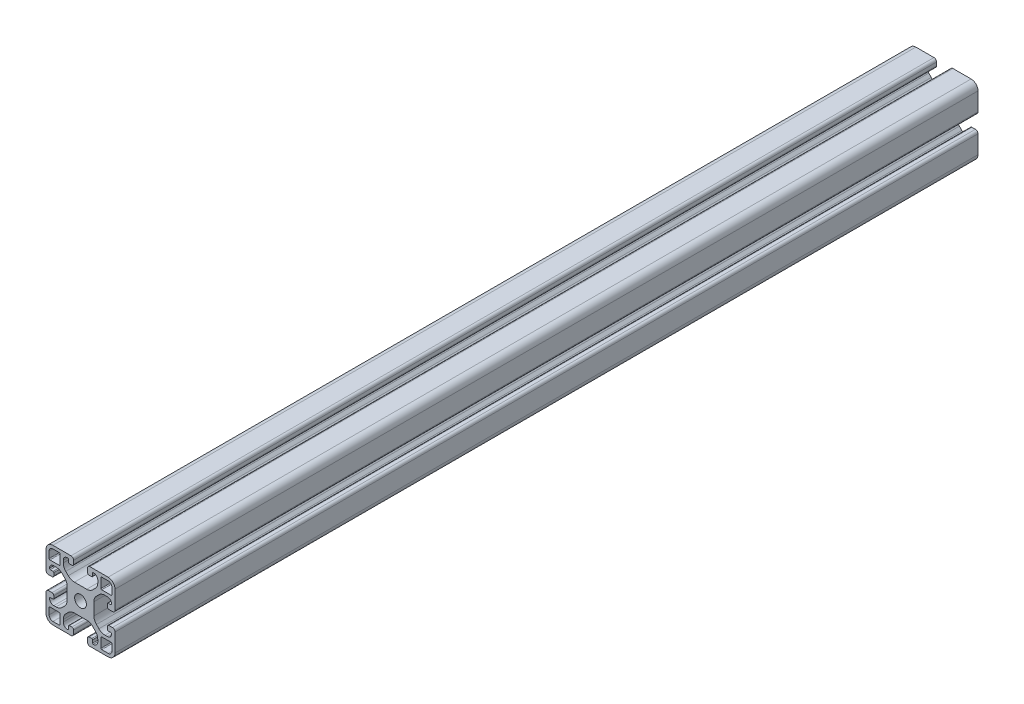
SolidWorks part; units mm, degrees
ref_plane "Plan de face" through (0, 0, 0) normal (0, 0, 1) x (1, 0, 0)
ref_plane "Plan de dessus" through (0, 0, 0) normal (0, 1, 0) x (1, 0, 0)
ref_plane "Plan de droite" through (0, 0, 0) normal (1, 0, 0) x (0, 0, -1)
ref_plane "Plan1" through (0, 0, -30) normal (0, 0, -1) x (-1, 0, 0)
sketch "Esquisse1" plane through (0, 0, -30) normal (0, 0, -1) x (-1, 0, 0)
  line L0 (-4.5, 15) -> (-4.5, 13.5)
  line L1 (-4, 13) -> (-2.5, 13)
  line L2 (-4.5, 10) -> (-5.8076, 10)
  line L3 (-9.3431, 11.4645) -> (-10.7855, 12.9069)
  line L4 (-12.25, 16.4424) -> (-12.25, 23.5576)
  line L5 (-10.7855, 27.0931) -> (-9.3431, 28.5355)
  line L6 (-5.8076, 30) -> (-4.5, 30)
  line L7 (-2.5, 27) -> (-4, 27)
  line L8 (-4.5, 26.5) -> (-4.5, 25)
  line L9 (-3.5, 24) -> (-1.5, 24)
  line L10 (0, 25.5) -> (0, 36)
  line L11 (-4, 40) -> (-14.5, 40)
  line L12 (-16, 38.5) -> (-16, 36.5)
  line L13 (-15, 35.5) -> (-13.5, 35.5)
  line L14 (-13, 36) -> (-13, 37.5)
  line L15 (-10, 35.5) -> (-10, 34.1924)
  line L16 (-11.4645, 30.6569) -> (-12.9069, 29.2145)
  line L17 (-16.4424, 27.75) -> (-23.5576, 27.75)
  line L18 (-27.0931, 29.2145) -> (-28.5355, 30.6569)
  line L19 (-30, 34.1924) -> (-30, 35.5)
  line L20 (-27, 37.5) -> (-27, 36)
  line L21 (-26.5, 35.5) -> (-25, 35.5)
  line L22 (-24, 36.5) -> (-24, 38.5)
  line L23 (-25.5, 40) -> (-36, 40)
  line L24 (-40, 36) -> (-40, 25.5)
  line L25 (-38.5, 24) -> (-36.5, 24)
  line L26 (-35.5, 25) -> (-35.5, 26.5)
  line L27 (-36, 27) -> (-37.5, 27)
  line L28 (-35.5, 30) -> (-34.1924, 30)
  line L29 (-30.6569, 28.5355) -> (-29.2145, 27.0931)
  line L30 (-27.75, 23.5576) -> (-27.75, 16.4424)
  line L31 (-29.2145, 12.9069) -> (-30.6569, 11.4645)
  line L32 (-34.1924, 10) -> (-35.5, 10)
  line L33 (-37.5, 13) -> (-36, 13)
  line L34 (-35.5, 13.5) -> (-35.5, 15)
  line L35 (-36.5, 16) -> (-38.5, 16)
  line L36 (-40, 14.5) -> (-40, 4)
  line L37 (-36, 0) -> (-25.5, 0)
  line L38 (-24, 1.5) -> (-24, 3.5)
  line L39 (-25, 4.5) -> (-26.5, 4.5)
  line L40 (-27, 4) -> (-27, 2.5)
  line L41 (-30, 4.5) -> (-30, 5.8076)
  line L42 (-28.5355, 9.3431) -> (-27.0931, 10.7855)
  line L43 (-23.5576, 12.25) -> (-16.4424, 12.25)
  line L44 (-12.9069, 10.7855) -> (-11.4645, 9.3431)
  line L45 (-10, 5.8076) -> (-10, 4.5)
  line L46 (-13, 2.5) -> (-13, 4)
  line L47 (-13.5, 4.5) -> (-15, 4.5)
  line L48 (-16, 3.5) -> (-16, 1.5)
  line L49 (-14.5, 0) -> (-4, 0)
  line L50 (0, 4) -> (0, 14.5)
  line L51 (-1.5, 16) -> (-3.5, 16)
  line L52 (-4, 1.8) -> (-7.7, 1.8)
  line L53 (-8.2, 2.3) -> (-8.2, 7.7)
  line L54 (-7.7, 8.2) -> (-2.3, 8.2)
  line L55 (-1.8, 7.7) -> (-1.8, 4)
  line L56 (-38.2, 4) -> (-38.2, 7.7)
  line L57 (-37.7, 8.2) -> (-32.3, 8.2)
  line L58 (-31.8, 7.7) -> (-31.8, 2.3)
  line L59 (-32.3, 1.8) -> (-36, 1.8)
  line L60 (-36, 38.2) -> (-32.3, 38.2)
  line L61 (-31.8, 37.7) -> (-31.8, 32.3)
  line L62 (-32.3, 31.8) -> (-37.7, 31.8)
  line L63 (-38.2, 32.3) -> (-38.2, 36)
  line L64 (-1.8, 36) -> (-1.8, 32.3)
  line L65 (-2.3, 31.8) -> (-7.7, 31.8)
  line L66 (-8.2, 32.3) -> (-8.2, 37.7)
  line L67 (-7.7, 38.2) -> (-4, 38.2)
  arc A0 (-4.5, 13.5) -> (-4, 13) centre (-4, 13.5) ccw
  arc A1 (-2.5, 13) -> (-2, 12.5) centre (-2.5, 12.5) cw
  arc A2 (-2, 12.5) -> (-4.5, 10) centre (-4.5, 12.5) cw
  arc A3 (-5.8076, 10) -> (-9.3431, 11.4645) centre (-5.8076, 15) cw
  arc A4 (-10.7855, 12.9069) -> (-12.25, 16.4424) centre (-7.25, 16.4424) cw
  arc A5 (-12.25, 23.5576) -> (-10.7855, 27.0931) centre (-7.25, 23.5576) cw
  arc A6 (-9.3431, 28.5355) -> (-5.8076, 30) centre (-5.8076, 25) cw
  arc A7 (-4.5, 30) -> (-2, 27.5) centre (-4.5, 27.5) cw
  arc A8 (-2, 27.5) -> (-2.5, 27) centre (-2.5, 27.5) cw
  arc A9 (-4, 27) -> (-4.5, 26.5) centre (-4, 26.5) ccw
  arc A10 (-4.5, 25) -> (-3.5, 24) centre (-3.5, 25) ccw
  arc A11 (-1.5, 24) -> (0, 25.5) centre (-1.5, 25.5) ccw
  arc A12 (0, 36) -> (-4, 40) centre (-4, 36) ccw
  arc A13 (-14.5, 40) -> (-16, 38.5) centre (-14.5, 38.5) ccw
  arc A14 (-16, 36.5) -> (-15, 35.5) centre (-15, 36.5) ccw
  arc A15 (-13.5, 35.5) -> (-13, 36) centre (-13.5, 36) ccw
  arc A16 (-13, 37.5) -> (-12.5, 38) centre (-12.5, 37.5) cw
  arc A17 (-12.5, 38) -> (-10, 35.5) centre (-12.5, 35.5) cw
  arc A18 (-10, 34.1924) -> (-11.4645, 30.6569) centre (-15, 34.1924) cw
  arc A19 (-12.9069, 29.2145) -> (-16.4424, 27.75) centre (-16.4424, 32.75) cw
  arc A20 (-23.5576, 27.75) -> (-27.0931, 29.2145) centre (-23.5576, 32.75) cw
  arc A21 (-28.5355, 30.6569) -> (-30, 34.1924) centre (-25, 34.1924) cw
  arc A22 (-30, 35.5) -> (-27.5, 38) centre (-27.5, 35.5) cw
  arc A23 (-27.5, 38) -> (-27, 37.5) centre (-27.5, 37.5) cw
  arc A24 (-27, 36) -> (-26.5, 35.5) centre (-26.5, 36) ccw
  arc A25 (-25, 35.5) -> (-24, 36.5) centre (-25, 36.5) ccw
  arc A26 (-24, 38.5) -> (-25.5, 40) centre (-25.5, 38.5) ccw
  arc A27 (-36, 40) -> (-40, 36) centre (-36, 36) ccw
  arc A28 (-40, 25.5) -> (-38.5, 24) centre (-38.5, 25.5) ccw
  arc A29 (-36.5, 24) -> (-35.5, 25) centre (-36.5, 25) ccw
  arc A30 (-35.5, 26.5) -> (-36, 27) centre (-36, 26.5) ccw
  arc A31 (-37.5, 27) -> (-38, 27.5) centre (-37.5, 27.5) cw
  arc A32 (-38, 27.5) -> (-35.5, 30) centre (-35.5, 27.5) cw
  arc A33 (-34.1924, 30) -> (-30.6569, 28.5355) centre (-34.1924, 25) cw
  arc A34 (-29.2145, 27.0931) -> (-27.75, 23.5576) centre (-32.75, 23.5576) cw
  arc A35 (-27.75, 16.4424) -> (-29.2145, 12.9069) centre (-32.75, 16.4424) cw
  arc A36 (-30.6569, 11.4645) -> (-34.1924, 10) centre (-34.1924, 15) cw
  arc A37 (-35.5, 10) -> (-38, 12.5) centre (-35.5, 12.5) cw
  arc A38 (-38, 12.5) -> (-37.5, 13) centre (-37.5, 12.5) cw
  arc A39 (-36, 13) -> (-35.5, 13.5) centre (-36, 13.5) ccw
  arc A40 (-35.5, 15) -> (-36.5, 16) centre (-36.5, 15) ccw
  arc A41 (-38.5, 16) -> (-40, 14.5) centre (-38.5, 14.5) ccw
  arc A42 (-40, 4) -> (-36, 0) centre (-36, 4) ccw
  arc A43 (-25.5, 0) -> (-24, 1.5) centre (-25.5, 1.5) ccw
  arc A44 (-24, 3.5) -> (-25, 4.5) centre (-25, 3.5) ccw
  arc A45 (-26.5, 4.5) -> (-27, 4) centre (-26.5, 4) ccw
  arc A46 (-27, 2.5) -> (-27.5, 2) centre (-27.5, 2.5) cw
  arc A47 (-27.5, 2) -> (-30, 4.5) centre (-27.5, 4.5) cw
  arc A48 (-30, 5.8076) -> (-28.5355, 9.3431) centre (-25, 5.8076) cw
  arc A49 (-27.0931, 10.7855) -> (-23.5576, 12.25) centre (-23.5576, 7.25) cw
  arc A50 (-16.4424, 12.25) -> (-12.9069, 10.7855) centre (-16.4424, 7.25) cw
  arc A51 (-11.4645, 9.3431) -> (-10, 5.8076) centre (-15, 5.8076) cw
  arc A52 (-10, 4.5) -> (-12.5, 2) centre (-12.5, 4.5) cw
  arc A53 (-12.5, 2) -> (-13, 2.5) centre (-12.5, 2.5) cw
  arc A54 (-13, 4) -> (-13.5, 4.5) centre (-13.5, 4) ccw
  arc A55 (-15, 4.5) -> (-16, 3.5) centre (-15, 3.5) ccw
  arc A56 (-16, 1.5) -> (-14.5, 0) centre (-14.5, 1.5) ccw
  arc A57 (-4, 0) -> (0, 4) centre (-4, 4) ccw
  arc A58 (0, 14.5) -> (-1.5, 16) centre (-1.5, 14.5) ccw
  arc A59 (-3.5, 16) -> (-4.5, 15) centre (-3.5, 15) ccw
  circle A60 centre (-20, 20) radius 3.4
  arc A61 (-1.8, 4) -> (-4, 1.8) centre (-4, 4) cw
  arc A62 (-7.7, 1.8) -> (-8.2, 2.3) centre (-7.7, 2.3) cw
  arc A63 (-8.2, 7.7) -> (-7.7, 8.2) centre (-7.7, 7.7) cw
  arc A64 (-2.3, 8.2) -> (-1.8, 7.7) centre (-2.3, 7.7) cw
  arc A65 (-36, 1.8) -> (-38.2, 4) centre (-36, 4) cw
  arc A66 (-38.2, 7.7) -> (-37.7, 8.2) centre (-37.7, 7.7) cw
  arc A67 (-32.3, 8.2) -> (-31.8, 7.7) centre (-32.3, 7.7) cw
  arc A68 (-31.8, 2.3) -> (-32.3, 1.8) centre (-32.3, 2.3) cw
  arc A69 (-38.2, 36) -> (-36, 38.2) centre (-36, 36) cw
  arc A70 (-32.3, 38.2) -> (-31.8, 37.7) centre (-32.3, 37.7) cw
  arc A71 (-31.8, 32.3) -> (-32.3, 31.8) centre (-32.3, 32.3) cw
  arc A72 (-37.7, 31.8) -> (-38.2, 32.3) centre (-37.7, 32.3) cw
  arc A73 (-4, 38.2) -> (-1.8, 36) centre (-4, 36) cw
  arc A74 (-1.8, 32.3) -> (-2.3, 31.8) centre (-2.3, 32.3) cw
  arc A75 (-7.7, 31.8) -> (-8.2, 32.3) centre (-7.7, 32.3) cw
  arc A76 (-8.2, 37.7) -> (-7.7, 38.2) centre (-7.7, 37.7) cw
extrude "Boss.-Extru.1" add sketch "Esquisse1" against normal blind 500
